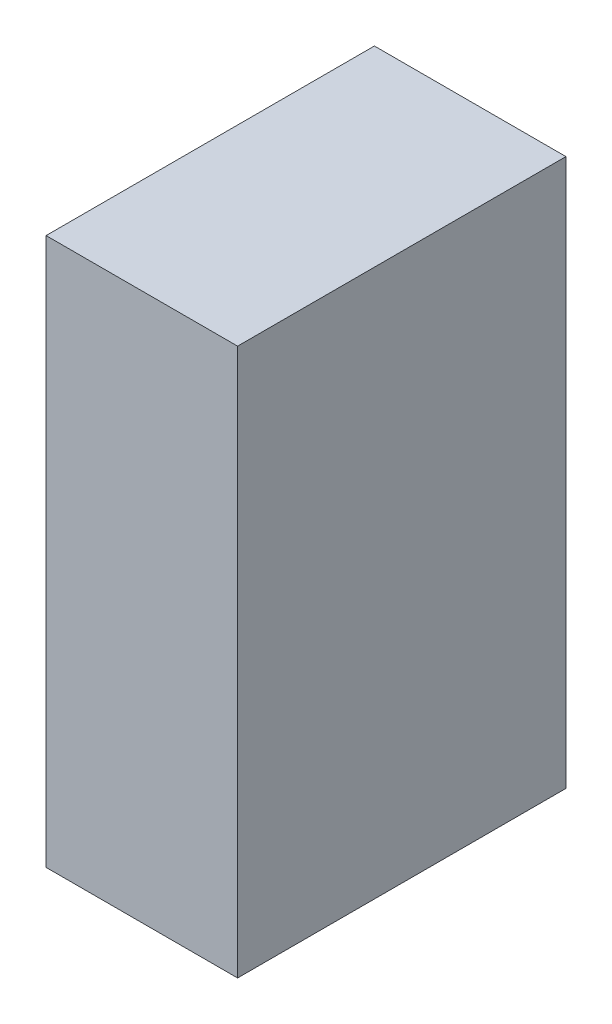
SolidWorks part; units mm, degrees
ref_plane "Front Plane" through (0, 0, 0) normal (0, 0, 1) x (1, 0, 0)
ref_plane "Top Plane" through (0, 0, 0) normal (0, 1, 0) x (1, 0, 0)
ref_plane "Right Plane" through (0, 0, 0) normal (1, 0, 0) x (0, 0, -1)
other "Configuration Table"
sketch "Sketch1" plane through (0, 0, 0) normal (0, 0, 1) x (1, 0, 0)
  line L1 (520, 180) -> (555, 180)
  line L2 (520, 180) -> (520, 280)
  line L3 (520, 280) -> (555, 280)
  line L4 (555, 180) -> (555, 280)
extrude "PACK_pano_servo_surucu_1_1" add sketch "Sketch1" against normal blind 60 from offset 188 separate body
